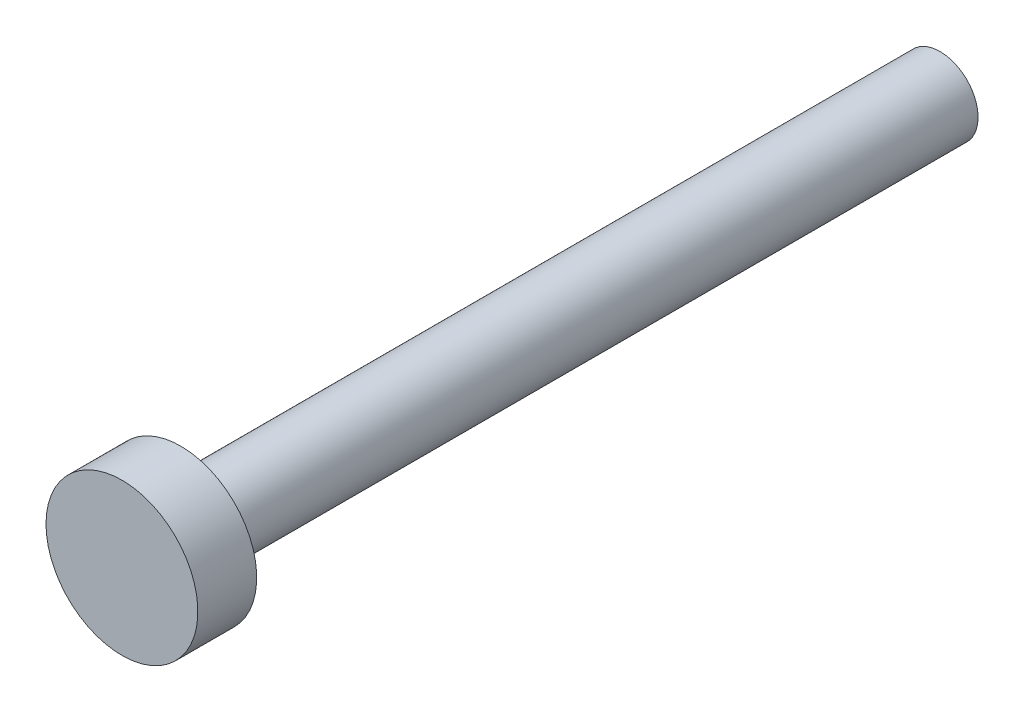
SolidWorks part; units mm, degrees
ref_plane "Plan de face" through (0, 0, 0) normal (0, 0, 1) x (1, 0, 0)
ref_plane "Plan de dessus" through (0, 0, 0) normal (0, 1, 0) x (1, 0, 0)
ref_plane "Plan de droite" through (0, 0, 0) normal (1, 0, 0) x (0, 0, -1)
sketch "Esquisse1" plane through (0, 0, 0) normal (0, 0, 1) x (1, 0, 0)
  circle A0 centre (0, 0) radius 4
  dimension "D1" = 8
extrude "Boss.-Extru.1" add sketch "Esquisse1" along normal blind 3.1
sketch "Esquisse2" plane through (0, 0, 0) normal (0, 0, -1) x (-1, 0, 0)
  circle A0 centre (0, 0) radius 2
  dimension "D1" = 4
extrude "Boss.-Extru.2" add sketch "Esquisse2" along normal blind 40
